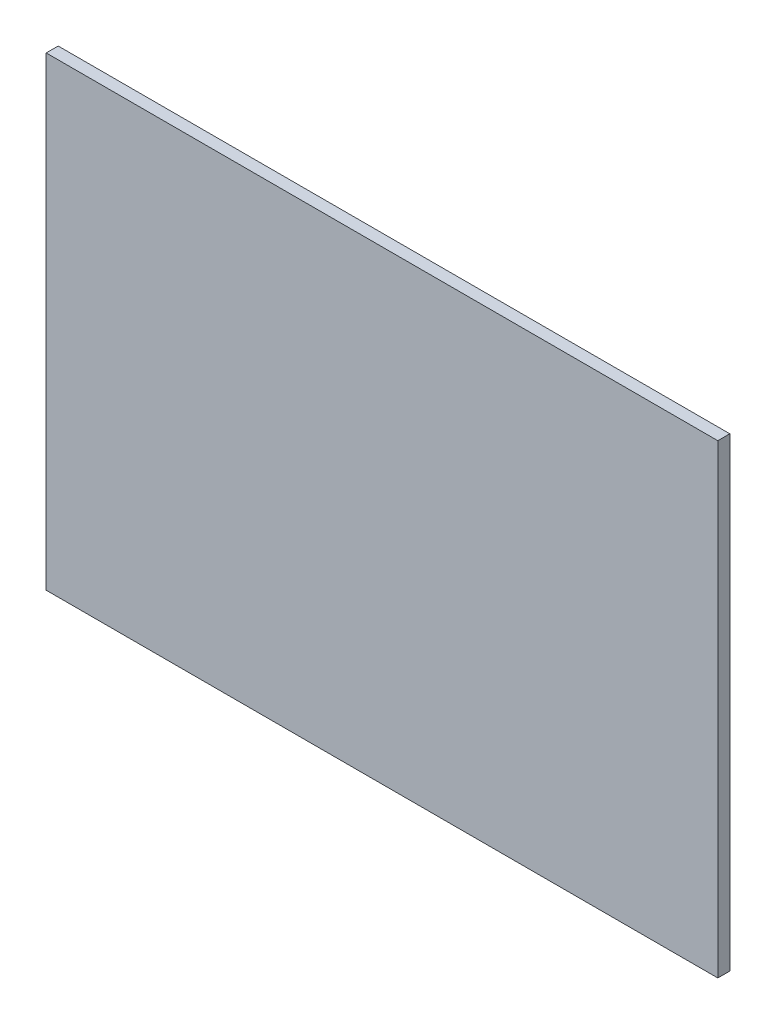
SolidWorks part; units mm, degrees
ref_plane "Front Plane" through (0, 0, 0) normal (0, 0, 1) x (1, 0, 0)
ref_plane "Top Plane" through (0, 0, 0) normal (0, 1, 0) x (1, 0, 0)
ref_plane "Right Plane" through (0, 0, 0) normal (1, 0, 0) x (0, 0, -1)
sketch "Sketch1" plane through (0, 0, 0) normal (0, 0, 1) x (1, 0, 0)
  line L1 (0, 0) -> (177.8, 0)
  line L2 (0, 0) -> (0, 123.19)
  line L3 (0, 123.19) -> (177.8, 123.19)
  line L4 (177.8, 0) -> (177.8, 123.19)
  dimension "D1" = 177.8
  dimension "D2" = 123.19
extrude "Boss-Extrude1" add sketch "Sketch1" along normal blind 3.175
